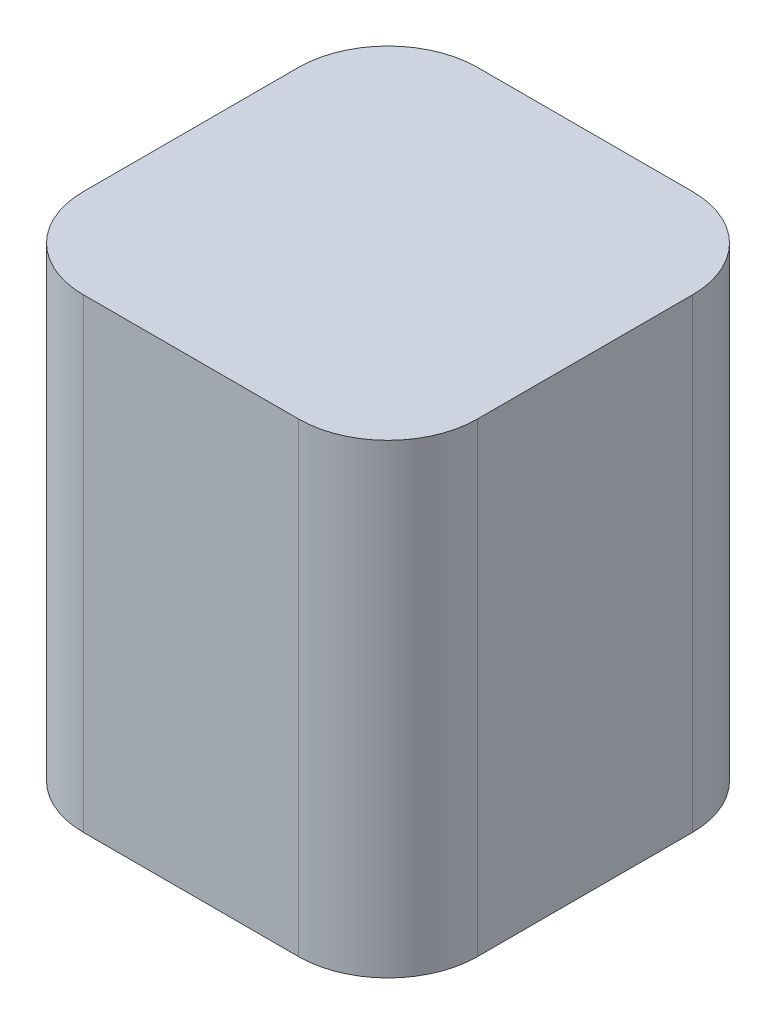
SolidWorks part; units mm, degrees
ref_plane "Front" through (0, 0, 0) normal (0, 0, 1) x (1, 0, 0)
ref_plane "Top" through (0, 0, 0) normal (0, 1, 0) x (1, 0, 0)
ref_plane "Right" through (0, 0, 0) normal (1, 0, 0) x (0, 0, -1)
sketch "Sketch1" plane through (0, 0, 0) normal (0, 1, 0) x (1, 0, 0)
  line L1 (-27.94, -27.94) -> (27.94, -27.94)
  line L2 (-27.94, -27.94) -> (-27.94, 27.94)
  line L3 (-27.94, 27.94) -> (27.94, 27.94)
  line L4 (27.94, -27.94) -> (27.94, 27.94)
  line L5 (-27.94, -27.94) -> (27.94, 27.94) construction
  line L6 (-27.94, 27.94) -> (27.94, -27.94) construction
  point P0 (0, 0)
  dimension "D1" = 55.88
  dimension "D2" = 55.88
extrude "Boss-Extrude1" add sketch "Sketch1" along normal blind 66.04
fillet "Fillet1" radius 12.7 4 edges at (-27.94, 33.02, -27.94) (27.94, 33.02, -27.94) (-27.94, 33.02, 27.94) (27.94, 33.02, 27.94)
